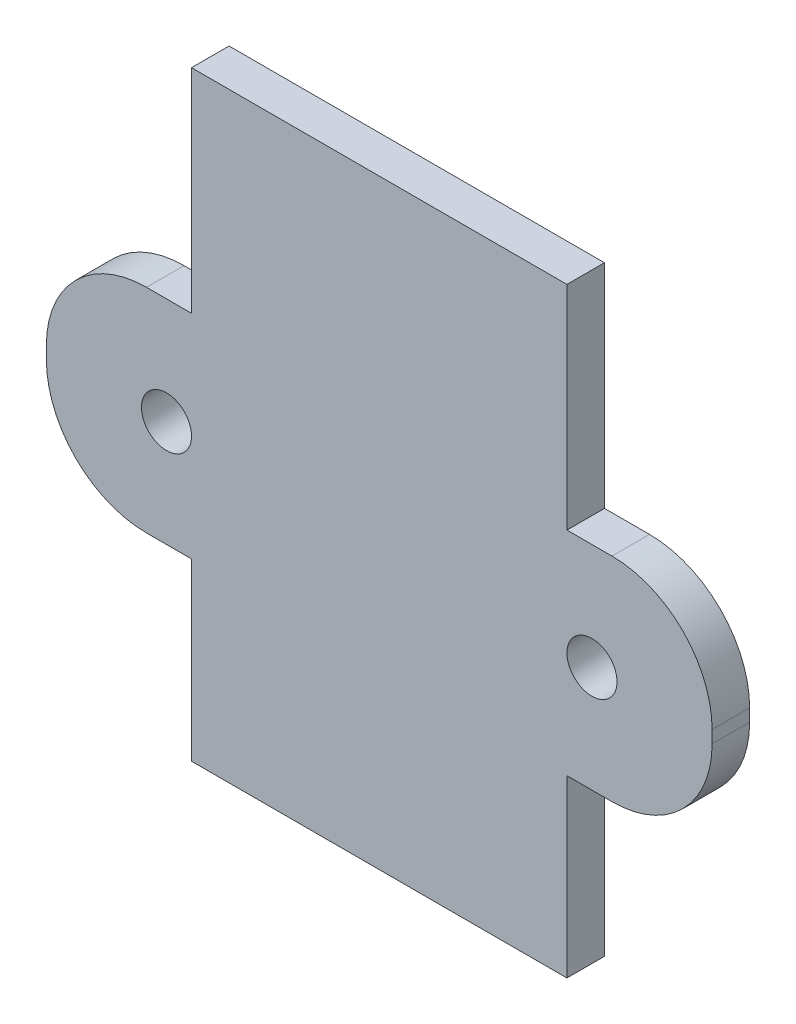
SolidWorks part; units mm, degrees
ref_plane "Front Plane" through (0, 0, 0) normal (0, 0, 1) x (1, 0, 0)
ref_plane "Top Plane" through (0, 0, 0) normal (0, 1, 0) x (1, 0, 0)
ref_plane "Right Plane" through (0, 0, 0) normal (1, 0, 0) x (0, 0, -1)
sketch "Esboço2" plane through (0, 0, 0) normal (0, 0, 1) x (1, 0, 0)
  line L1 (14.1221, 6.9721) -> (-14.1221, 6.9721)
  line L2 (14.1221, 6.9721) -> (14.1221, -6.9721)
  line L3 (14.1221, -6.9721) -> (-14.1221, -6.9721)
  line L4 (-14.1221, 6.9721) -> (-14.1221, -6.9721)
  line L5 (14.1221, 6.9721) -> (-14.1221, -6.9721) construction
  line L6 (14.1221, -6.9721) -> (-14.1221, 6.9721) construction
  point P0 (0, 0)
extrude "Ressalto-extrusão1" add sketch "Esboço2" along normal blind 2.54
sketch "Esboço3" plane through (0, 0, 0) normal (0, 0, 1) x (1, 0, 0)
  line L2 (-40.6382, 3.4522) -> (-42.4382, 3.4522)
  line L3 (-40.6382, 11.9522) -> (-40.6382, 3.4522)
  line L4 (-40.6382, 11.9522) -> (-25.6382, 11.9522)
  line L5 (-42.4382, -5.0478) -> (-39.1382, -5.0478)
  line L6 (-40.6382, 3.4522) -> (-40.6382, -5.0478) construction
  line L7 (-40.6382, -5.0478) -> (-40.6382, -12.0478)
  line L8 (-40.6382, -12.0478) -> (-25.6382, -12.0478)
  line L9 (-33.1382, 11.9522) -> (-33.1382, -12.0478) construction
  line L10 (-25.6382, 3.4522) -> (-25.6382, -5.0478) construction
  line L11 (-25.6382, -5.0478) -> (-25.6382, -12.0478)
  line L12 (-23.8382, -5.0478) -> (-27.1382, -5.0478)
  line L13 (-25.6382, 11.9522) -> (-25.6382, 3.4522)
  line L14 (-25.6382, 3.4522) -> (-23.8382, 3.4522)
  line L15 (-46.4382, -1.0478) -> (-46.4382, -0.5478)
  line L16 (-19.8382, -1.0478) -> (-19.8382, -0.5478)
  arc A2 (-46.4382, -1.0478) -> (-42.4382, -5.0478) centre (-42.4382, -1.0478) ccw
  arc A3 (-42.4382, 3.4522) -> (-46.4382, -0.5478) centre (-42.4382, -0.5478) ccw
  circle A4 centre (-41.6382, -0.7978) radius 1
  circle A5 centre (-24.6382, -0.7978) radius 1
  arc A6 (-23.8382, 3.4522) -> (-19.8382, -0.5478) centre (-23.8382, -0.5478) cw
  arc A7 (-19.8382, -1.0478) -> (-23.8382, -5.0478) centre (-23.8382, -1.0478) cw
extrude "Ressalto-extrusão2" add sketch "Esboço3" along normal blind 1.5 separate body
sketch "Esboço4" plane through (0, 0, 2.54) normal (0, 0, 1) x (1, 0, 0)
  line L4 (-14.1221, 6.9721) -> (-14.1221, -6.9721)
  line L5 (-14.1221, -6.9721) -> (14.1221, -6.9721)
  line L6 (14.1221, -6.9721) -> (14.1221, 6.9721)
  line L7 (14.1221, 6.9721) -> (-14.1221, 6.9721)
  line L8 (-14.1221, 6.9721) -> (-14.1221, -6.9721)
  line L9 (-14.1221, -6.9721) -> (14.1221, -6.9721)
  line L10 (14.1221, -6.9721) -> (14.1221, 6.9721)
  line L11 (14.1221, 6.9721) -> (-14.1221, 6.9721)
  dimension "D1" = 0
extrude "Corte-extrusão1" cut sketch "Esboço4" against normal up to surface (2.54 mm away) up to face at (0, 0, 0)
